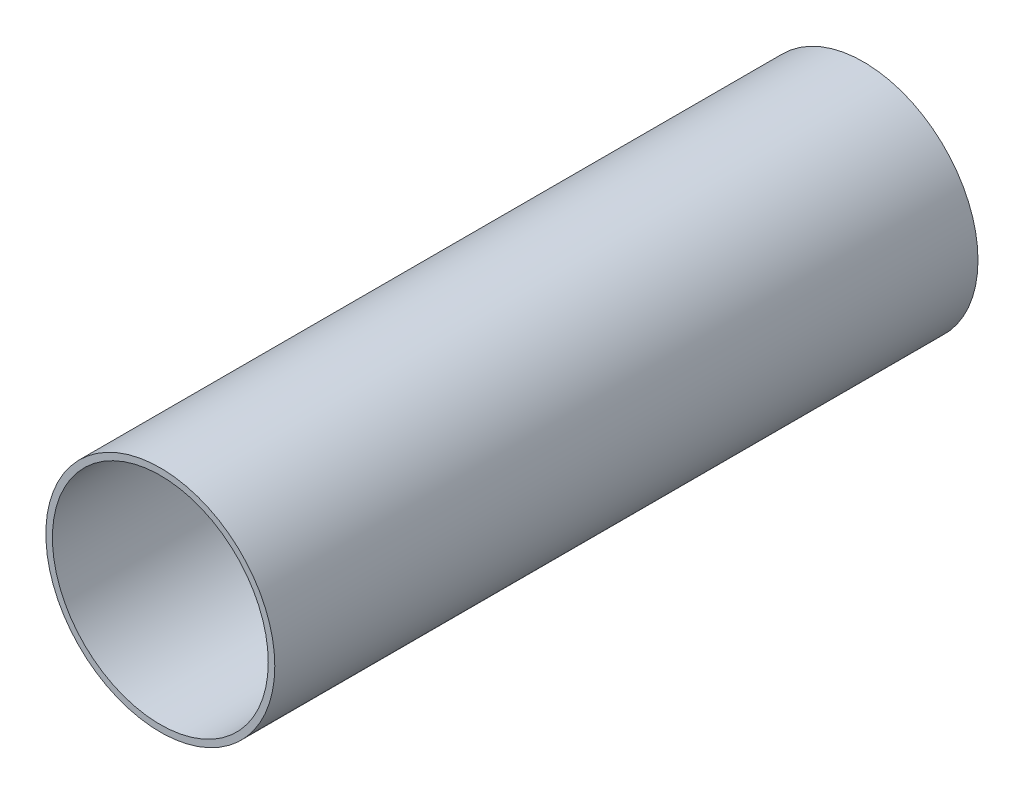
SolidWorks part; units mm, degrees
material "Q235A"
ref_plane "前视" through (0, 0, 0) normal (0, 0, 1) x (1, 0, 0)
ref_plane "上视" through (0, 0, 0) normal (0, 1, 0) x (1, 0, 0)
ref_plane "右视" through (0, 0, 0) normal (1, 0, 0) x (0, 0, -1)
sketch "草图1" plane through (0, 0, 0) normal (0, 0, 1) x (1, 0, 0)
  circle A0 centre (0, 0) radius 35
  circle A1 centre (0, 0) radius 33
  dimension "D1" = 66
  dimension "D2" = 70
extrude "凸台-拉伸1" add sketch "草图1" along normal blind 215
